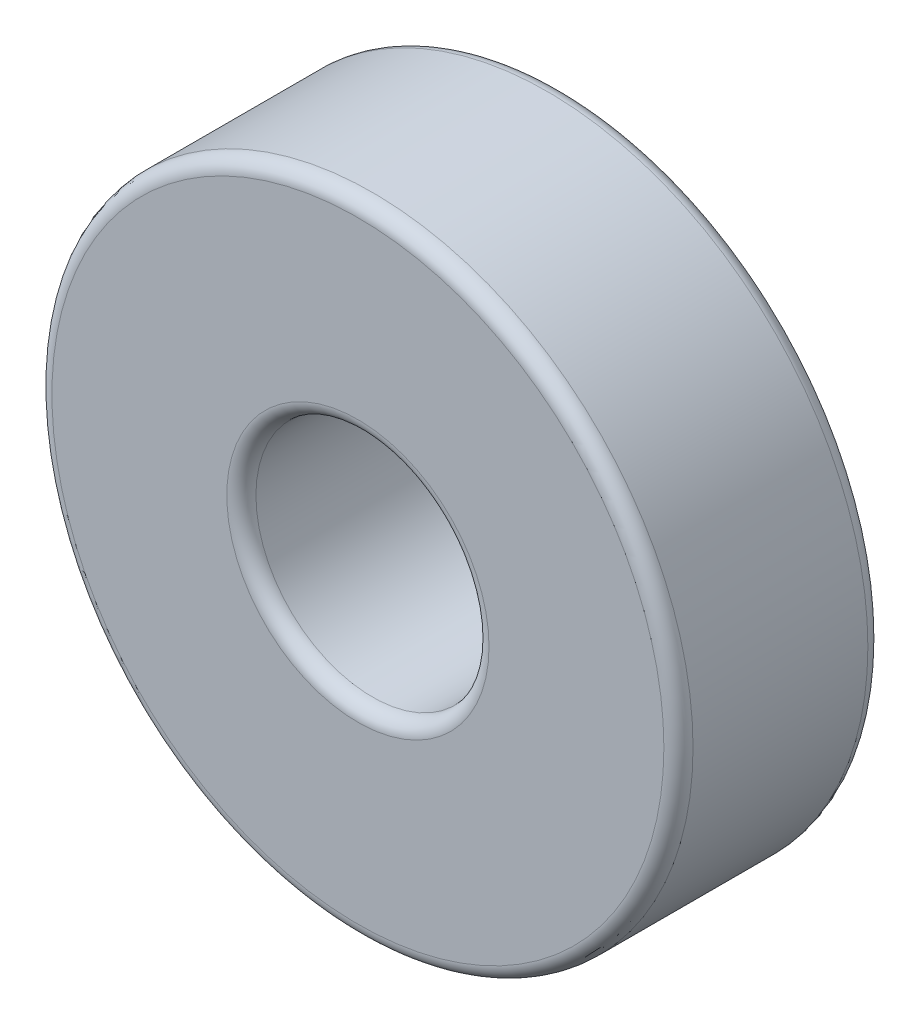
SolidWorks part; units mm, degrees
ref_plane "Alzado" through (0, 0, 0) normal (0, 0, 1) x (1, 0, 0)
ref_plane "Planta" through (0, 0, 0) normal (0, 1, 0) x (1, 0, 0)
ref_plane "Vista lateral" through (0, 0, 0) normal (1, 0, 0) x (0, 0, -1)
sketch "Croquis1" plane through (0, 0, 0) normal (0, 0, 1) x (1, 0, 0)
  circle A0 centre (0, 0) radius 4
  circle A1 centre (0, 0) radius 11
  dimension "D1" = 8
  dimension "D2" = 22
extrude "Saliente-Extruir1" add sketch "Croquis1" along normal blind 7
fillet "Redondeo1" radius 0.5 4 edges at (4, 0, 7) (4, 0, 0) (11, 0, 0) (11, 0, 7)
